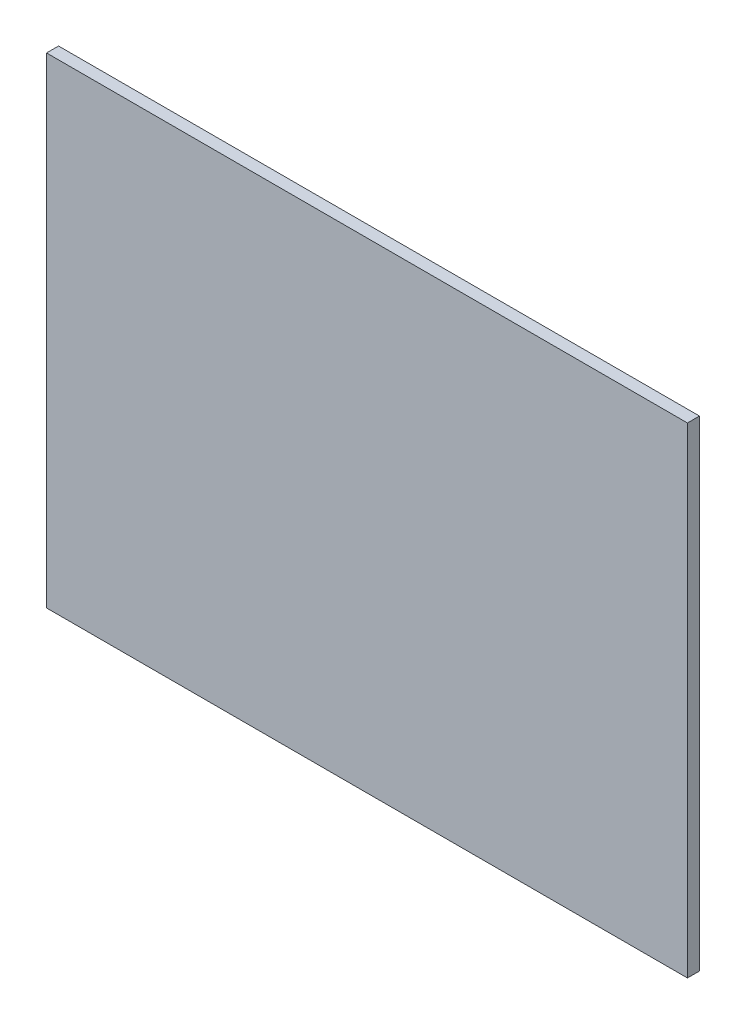
SolidWorks part; units mm, degrees
material "Maple"
ref_plane "Front Plane" through (0, 0, 0) normal (0, 0, 1) x (1, 0, 0)
ref_plane "Top Plane" through (0, 0, 0) normal (0, 1, 0) x (1, 0, 0)
ref_plane "Right Plane" through (0, 0, 0) normal (1, 0, 0) x (0, 0, -1)
sketch "Sketch1" plane through (0, 0, 0) normal (0, 0, 1) x (1, 0, 0)
  line L1 (0, 0) -> (1016, 0)
  line L2 (0, 0) -> (0, 762)
  line L3 (0, 762) -> (1016, 762)
  line L4 (1016, 0) -> (1016, 762)
  dimension "D1" = 1016
  dimension "D2" = 762
extrude "Boss-Extrude1" add sketch "Sketch1" along normal blind 19.05
